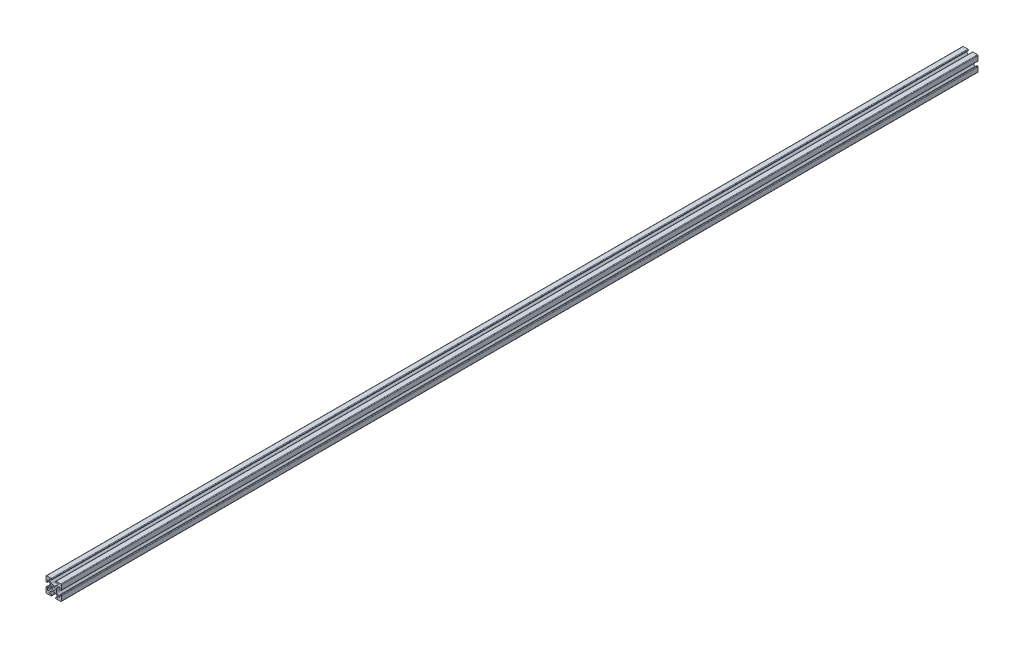
SolidWorks part; units mm, degrees
ref_plane "Front" through (0, 0, 0) normal (0, 0, 1) x (1, 0, 0)
ref_plane "Top" through (0, 0, 0) normal (0, 1, 0) x (1, 0, 0)
ref_plane "Right" through (0, 0, 0) normal (1, 0, 0) x (0, 0, -1)
sketch "Sketch1" plane through (0, 0, 0) normal (0, 0, 1) x (1, 0, 0)
  line L0 (0, 0) -> (25.4, 0) construction
  line L1 (25.4, 0) -> (25.4, 25.4) construction
  line L2 (25.4, 25.4) -> (0, 25.4) construction
  line L3 (0, 25.4) -> (0, 0) construction
  line L4 (12.7, 0) -> (12.7, 12.7) construction
  line L5 (12.7, 0) -> (15.9385, 0) construction
  line L6 (15.9385, 0) -> (15.9385, 25.4) construction
  line L7 (15.9385, 25.4) -> (9.4615, 25.4) construction
  line L8 (9.4615, 25.4) -> (9.4615, 0) construction
  line L9 (25.4, 25.4) -> (0, 0) construction
  line L10 (24.6187, 26.1813) -> (-0.7813, 0.7813)
  line L11 (26.1813, 24.6187) -> (0.7813, -0.7813)
  line L12 (0, 25.4) -> (25.4, 0) construction
  line L13 (-0.7813, 24.6187) -> (24.6187, -0.7813)
  line L14 (0.7813, 26.1813) -> (26.1813, 0.7813)
  line L15 (9.4615, 25.4) -> (0, 25.4) construction
  line L16 (15.9385, 25.4) -> (25.4, 25.4) construction
  line L17 (12.7, 12.7) -> (12.7, 17.2085) construction
  line L18 (12.7, 17.2085) -> (17.2085, 17.2085) construction
  line L19 (17.2085, 17.2085) -> (17.2085, 8.1915) construction
  line L20 (17.2085, 8.1915) -> (8.1915, 8.1915) construction
  line L21 (8.1915, 8.1915) -> (8.1915, 17.2085) construction
  line L22 (8.1915, 17.2085) -> (12.7, 17.2085) construction
  line L23 (8.1915, 8.1915) -> (2.3495, 8.1915) construction
  line L24 (2.3495, 8.1915) -> (2.3495, 0) construction
  line L25 (2.3495, 8.1915) -> (2.3495, 25.4) construction
  line L26 (17.2085, 8.1915) -> (23.0505, 8.1915) construction
  line L27 (23.0505, 8.1915) -> (23.0505, 25.4) construction
  line L28 (23.0505, 8.1915) -> (23.0505, 0) construction
  line L29 (17.2085, 8.1915) -> (17.2085, 2.3495) construction
  line L30 (17.2085, 2.3495) -> (25.4, 2.3495) construction
  line L31 (17.2085, 2.3495) -> (0, 2.3495) construction
  line L32 (17.2085, 17.2085) -> (17.2085, 23.0505) construction
  line L33 (17.2085, 23.0505) -> (25.4, 23.0505) construction
  line L34 (17.2085, 23.0505) -> (0, 23.0505) construction
  line L35 (12.7, 12.7) -> (12.7, 9.4615) construction
  line L36 (12.7, 9.4615) -> (25.4, 9.4615) construction
  line L37 (25.4, 9.4615) -> (25.4, 15.9385) construction
  line L38 (25.4, 15.9385) -> (0, 15.9385) construction
  line L39 (12.7, 9.4615) -> (0, 9.4615) construction
  line L40 (9.4615, 25.4) -> (0, 25.4)
  line L41 (15.9385, 25.4) -> (25.4, 25.4)
  line L42 (25.4, 25.4) -> (25.4, 15.9385)
  line L43 (25.4, 15.9385) -> (25.4, 25.4)
  line L44 (25.4, 9.4615) -> (25.4, 0)
  line L45 (25.4, 0) -> (15.9385, 0)
  line L46 (9.4615, 0) -> (0, 0)
  line L47 (0, 0) -> (0, 9.4615)
  line L48 (0, 15.9385) -> (0, 25.4)
  line L49 (2.3495, 9.4615) -> (2.3495, 3.9121)
  line L50 (3.9121, 2.3495) -> (9.4615, 2.3495)
  line L51 (15.9385, 2.3495) -> (21.4879, 2.3495)
  line L52 (23.0505, 3.9121) -> (23.0505, 9.4615)
  line L53 (23.0505, 9.4615) -> (25.4, 9.4615)
  line L54 (25.4, 15.9385) -> (23.0505, 15.9385)
  line L55 (23.0505, 15.9385) -> (23.0505, 21.4879)
  line L56 (21.4879, 23.0505) -> (15.9385, 23.0505)
  line L57 (15.9385, 23.0505) -> (15.9385, 25.4)
  line L58 (9.4615, 25.4) -> (9.4615, 23.0505)
  line L59 (9.4615, 23.0505) -> (3.9121, 23.0505)
  line L60 (2.3495, 21.4879) -> (2.3495, 15.9385)
  line L61 (2.3495, 15.9385) -> (0, 15.9385)
  line L62 (0, 9.4615) -> (2.3495, 9.4615)
  line L63 (9.4615, 2.3495) -> (9.4615, 0)
  line L64 (15.9385, 2.3495) -> (15.9385, 0)
  line L65 (8.1915, 15.6459) -> (8.1915, 9.7541)
  line L66 (9.7541, 8.1915) -> (15.6459, 8.1915)
  line L67 (17.2085, 9.7541) -> (17.2085, 15.6459)
  line L68 (15.6459, 17.2085) -> (9.7541, 17.2085)
  circle A0 centre (12.7, 12.7) radius 2.6035
  dimension "D1" = 1.1049
  dimension "D2" = 1.1049
  dimension "D3" = 1.1049
  dimension "D4" = 1.1049
extrude "Boss-Extrude1" add sketch "Sketch1" along normal blind 1524 contours L59 L58 L40 L14 | A0 L14 L40 L48 L13 | L61 L60 L13 L48 | A0 L10 L68 L14 | A0 L13 L65 L10 | A0 L10 L47 L46 L11 | A0 L11 L66 L13 | A0 L13 L45 L44 L14 | A0 L14 L67 L11 | A0 L11 L42 L41 L10 | L57 L56 L10 L41 | L55 L54 L42 L11 | L53 L52 L14 L44 | L51 L64 L45 L13 | L63 L50 L11 L46 | L62 L47 L10 L49
fillet "Fillet1" radius 2.54 8 edges at (8.1915, 9.7541, 762) (8.1915, 15.6459, 762) (9.7541, 8.1915, 762) (15.6459, 8.1915, 762) (17.2085, 9.7541, 762) (17.2085, 15.6459, 762) (15.6459, 17.2085, 762) (9.7541, 17.2085, 762)
fillet "Fillet2" radius 1.016 20 edges at (25.4, 15.9385, 762) (25.4, 0, 762) (9.4615, 0, 762) (2.3495, 15.9385, 762) (25.4, 25.4, 762) (15.9385, 25.4, 762) (15.9385, 23.0505, 762) (23.0505, 15.9385, 762) (25.4, 9.4615, 762) (23.0505, 9.4615, 762) (15.9385, 2.3495, 762) (15.9385, 0, 762) (0, 0, 762) (9.4615, 2.3495, 762) (2.3495, 9.4615, 762) (0, 9.4615, 762) (0, 15.9385, 762) (0, 25.4, 762) (9.4615, 23.0505, 762) (9.4615, 25.4, 762)
fillet "Fillet3" radius 1.016 8 edges at (2.3495, 3.9121, 762) (3.9121, 2.3495, 762) (23.0505, 3.9121, 762) (21.4879, 2.3495, 762) (23.0505, 21.4879, 762) (21.4879, 23.0505, 762) (2.3495, 21.4879, 762) (3.9121, 23.0505, 762)
